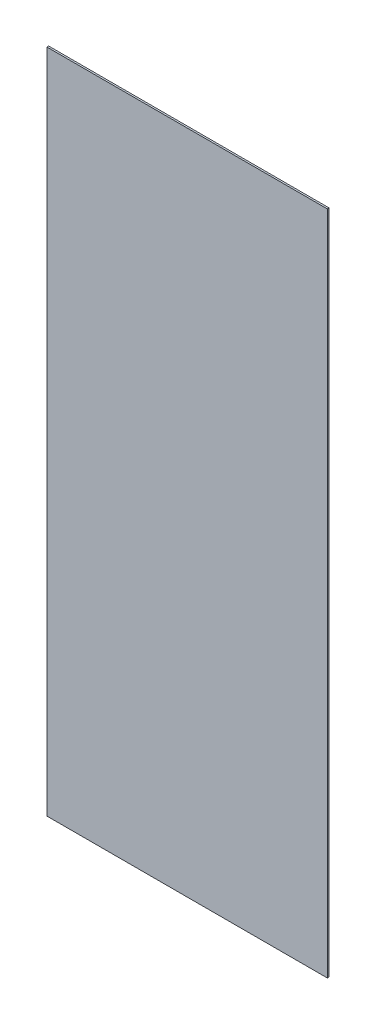
SolidWorks part; units mm, degrees
material "Akryl (Średnie-wysokie uderzenie)"
ref_plane "Płaszczyzna przednia" through (0, 0, 0) normal (0, 0, 1) x (1, 0, 0)
ref_plane "Płaszczyzna górna" through (0, 0, 0) normal (0, 1, 0) x (1, 0, 0)
ref_plane "Płaszczyzna prawa" through (0, 0, 0) normal (1, 0, 0) x (0, 0, -1)
sketch "Szkic1" plane through (0, 0, 0) normal (0, 0, 1) x (1, 0, 0)
  line L1 (0, 0) -> (800, 0)
  line L2 (0, 0) -> (0, 1900)
  line L3 (0, 1900) -> (800, 1900)
  line L4 (800, 0) -> (800, 1900)
  dimension "D1" = 1900
  dimension "D2" = 800
extrude "Dodanie-wyciągnięcie1" add sketch "Szkic1" along normal blind 5 contours L2 L3 L4 L1
